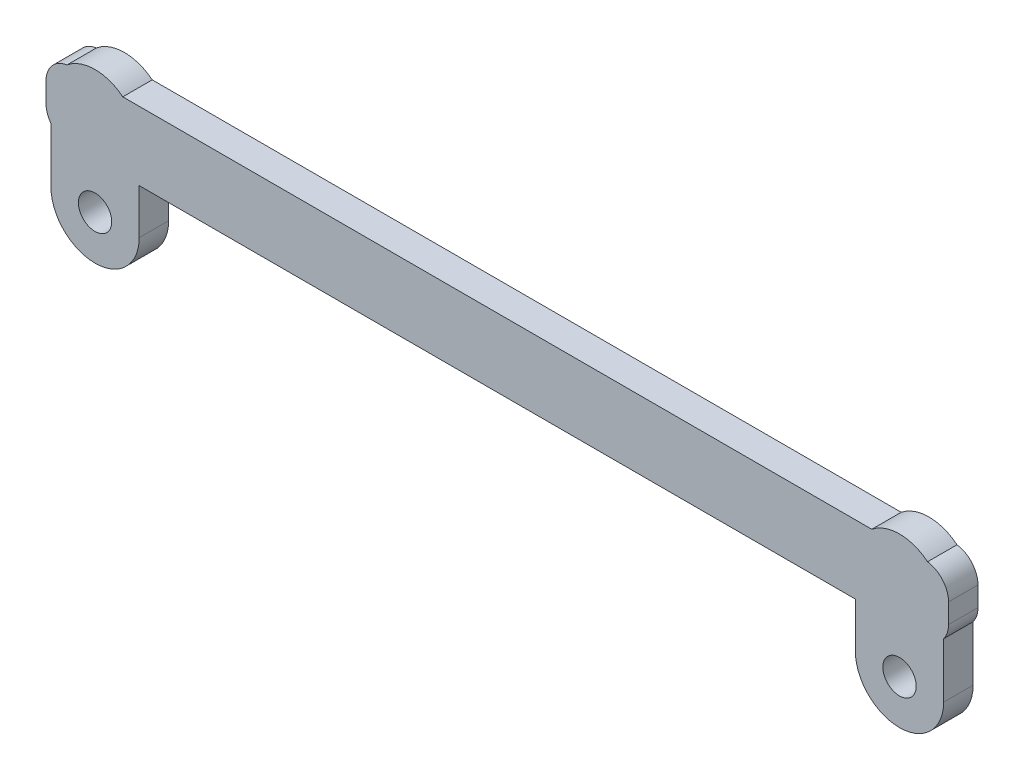
SolidWorks part; units mm, degrees
ref_plane "Front Plane" through (0, 0, 0) normal (0, 0, 1) x (1, 0, 0)
ref_plane "Top Plane" through (0, 0, 0) normal (0, 1, 0) x (1, 0, 0)
ref_plane "Right Plane" through (0, 0, 0) normal (1, 0, 0) x (0, 0, -1)
sketch "S01 - Removable upper crossbar" plane through (0, 0, 0) normal (0, 0, 1) x (1, 0, 0)
  line L0 (-43.5, -53.7) -> (43.5, -53.7)
  line L1 (46, -51.2) -> (46, -49.2)
  line L2 (43.5, -46.7) -> (-43.5, -46.7)
  line L3 (-46, -49.2) -> (-46, -51.2)
  arc A0 (43.5, -53.7) -> (46, -51.2) centre (43.5, -51.2) ccw
  arc A1 (46, -49.2) -> (43.5, -46.7) centre (43.5, -49.2) ccw
  arc A2 (-43.5, -46.7) -> (-46, -49.2) centre (-43.5, -49.2) ccw
  arc A3 (-46, -51.2) -> (-43.5, -53.7) centre (-43.5, -51.2) ccw
  dimension "D1" = 2.5
  dimension "D2" = 46
  dimension "D3" = 46
  dimension "D4" = 46.7
  dimension "D5" = 53.7
extrude "01 - Removable upper crossbar" add sketch "S01 - Removable upper crossbar" along normal blind 3
sketch "S02 - Fastening lug 0" plane through (0, 0, 0) normal (0, 0, 1) x (1, 0, 0)
  line L0 (-45.5, -58.3) -> (-45.5, -50.2)
  line L1 (-36.5, -50.2) -> (-36.5, -58.3)
  arc A0 (-45.5, -50.2) -> (-36.5, -50.2) centre (-41, -50.2) cw
  arc A1 (-36.5, -58.3) -> (-45.5, -58.3) centre (-41, -58.3) cw
  circle A2 centre (-41, -58.3) radius 1.7
  dimension "D1" = 3.4
  dimension "D2" = 4.5
  dimension "D3" = 41
  dimension "D4" = 50.2
  dimension "D5" = 58.3
extrude "02 - Fastening lug 0" add sketch "S02 - Fastening lug 0" along normal blind 3
sketch "S03 - Fastening lug 1" plane through (0, 0, 0) normal (0, 0, 1) x (1, 0, 0)
  line L0 (36.5, -58.3) -> (36.5, -50.2)
  line L1 (45.5, -50.2) -> (45.5, -58.3)
  arc A0 (36.5, -50.2) -> (45.5, -50.2) centre (41, -50.2) cw
  arc A1 (45.5, -58.3) -> (36.5, -58.3) centre (41, -58.3) cw
  circle A2 centre (41, -58.3) radius 1.7
  dimension "D1" = 3.4
  dimension "D2" = 4.5
  dimension "D3" = 41
  dimension "D4" = 50.2
  dimension "D5" = 58.3
extrude "03 - Fastening lug 1" add sketch "S03 - Fastening lug 1" along normal blind 3
